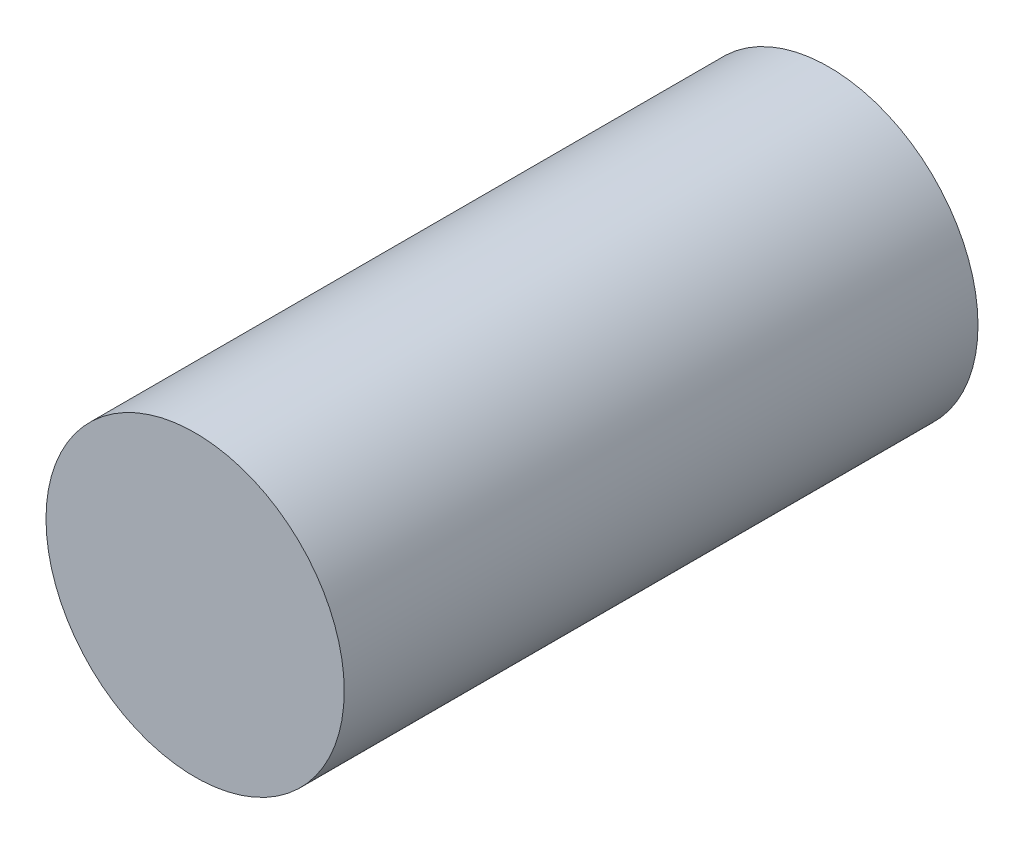
SolidWorks part; units mm, degrees
ref_plane "Plano frontal" through (0, 0, 0) normal (0, 0, 1) x (1, 0, 0)
ref_plane "Plano superior" through (0, 0, 0) normal (0, 1, 0) x (1, 0, 0)
ref_plane "Plano direito" through (0, 0, 0) normal (1, 0, 0) x (0, 0, -1)
sketch "Esboço1" plane through (0, 0, 0) normal (0, 0, 1) x (1, 0, 0)
  circle A0 centre (0, 0) radius 4
  dimension "D1" = 8
extrude "Ressalto-extrusão1" add sketch "Esboço1" along normal blind 17
